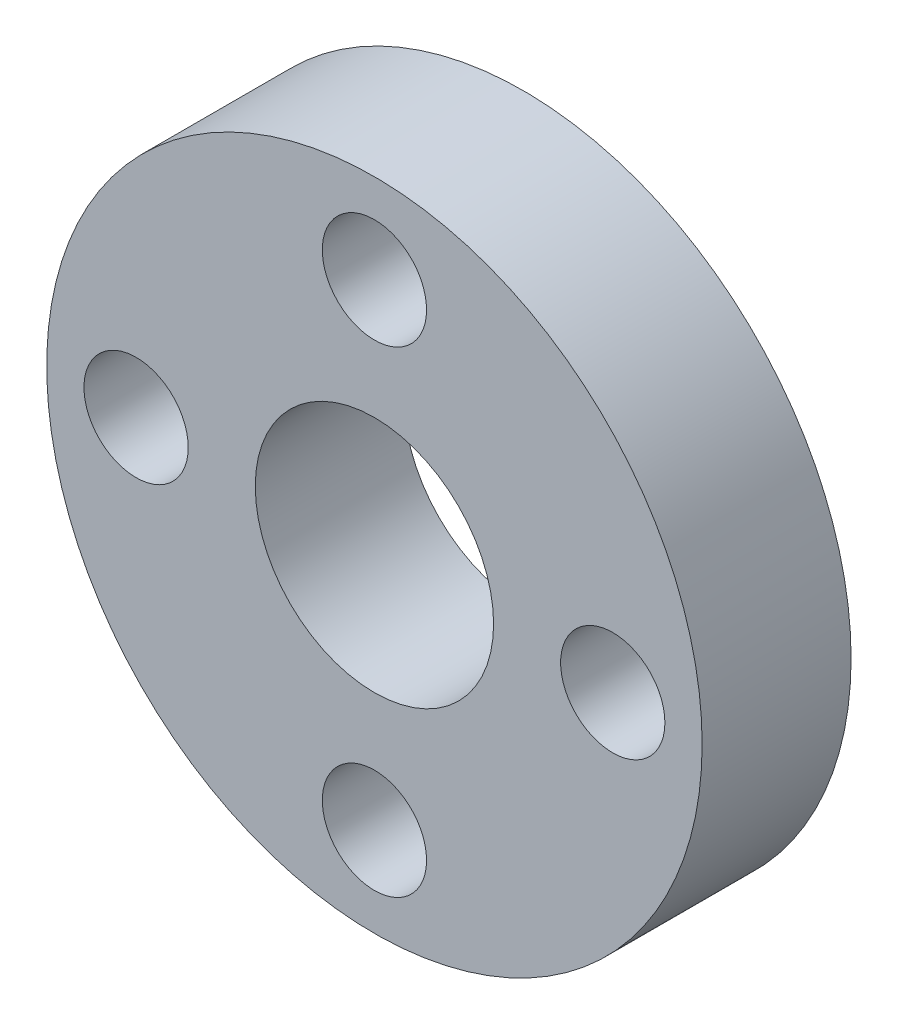
SolidWorks part; units mm, degrees
ref_plane "정면" through (0, 0, 0) normal (0, 0, 1) x (1, 0, 0)
ref_plane "윗면" through (0, 0, 0) normal (0, 1, 0) x (1, 0, 0)
ref_plane "우측면" through (0, 0, 0) normal (1, 0, 0) x (0, 0, -1)
sketch "스케치1" plane through (0, 0, 0) normal (0, 0, 1) x (1, 0, 0)
  circle A0 centre (0, 0) radius 11
  circle A1 centre (0, 8) radius 1.75
  circle A2 centre (8, 0) radius 1.75
  circle A3 centre (0, -8) radius 1.75
  circle A4 centre (-8, 0) radius 1.75
  point P14 (0, 0)
  dimension "D1" = 22
  dimension "D2" = 3.5
  dimension "D3" = 8
  dimension "D4" = 4
extrude "보스-돌출1" add sketch "스케치1" along normal blind 5
sketch "스케치2" plane through (0, 0, 5) normal (0, 0, 1) x (1, 0, 0)
  circle A0 centre (0, 0) radius 4
  circle A1 centre (0, 0) radius 2.35
  dimension "D1" = 4.7
  dimension "D2" = 8
extrude "컷-돌출1" cut sketch "스케치2" against normal blind 10 contours A1 | A0 A1
